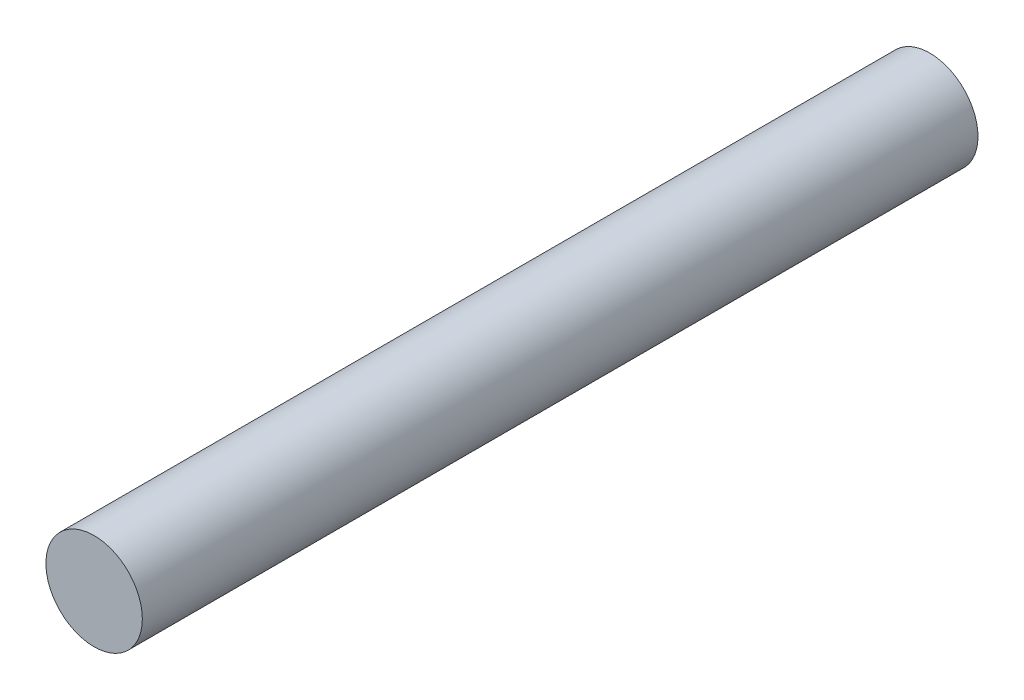
SolidWorks part; units mm, degrees
ref_plane "前视基准面" through (0, 0, 0) normal (0, 0, 1) x (1, 0, 0)
ref_plane "上视基准面" through (0, 0, 0) normal (0, 1, 0) x (1, 0, 0)
ref_plane "右视基准面" through (0, 0, 0) normal (1, 0, 0) x (0, 0, -1)
other "Configuration Table"
sketch "草图1" plane through (0, 0, 0) normal (0, 0, 1) x (1, 0, 0)
  circle A0 centre (0, 0) radius 3
extrude "凸台-拉伸1" add sketch "草图1" along normal blind 52
